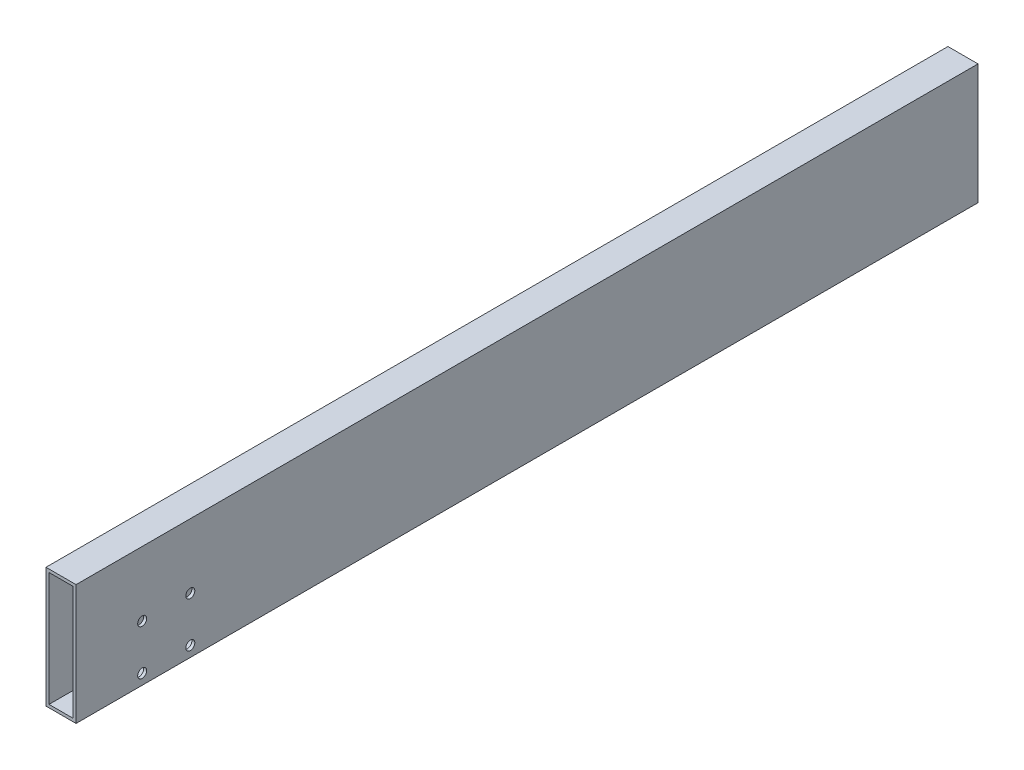
SolidWorks part; units mm, degrees
material "3.0205 (EN-AW 1200)"
ref_plane "前视基准面" through (0, 0, 0) normal (0, 0, 1) x (1, 0, 0)
ref_plane "上视基准面" through (0, 0, 0) normal (0, 1, 0) x (1, 0, 0)
ref_plane "右视基准面" through (0, 0, 0) normal (1, 0, 0) x (0, 0, -1)
sketch "草图1" plane through (0, 0, 0) normal (0, 0, 1) x (1, 0, 0)
  line L1 (0, 0) -> (10, 0)
  line L2 (0, 0) -> (0, 40)
  line L3 (0, 40) -> (10, 40)
  line L4 (10, 0) -> (10, 40)
  line L5 (1, 1) -> (9, 1)
  line L6 (1, 1) -> (1, 39)
  line L7 (1, 39) -> (9, 39)
  line L8 (9, 1) -> (9, 39)
  dimension "D1" = 10
  dimension "D2" = 40
  dimension "D3" = 1
  dimension "D4" = 1
  dimension "D5" = 1
  dimension "D6" = 1
extrude "凸台-拉伸1" add sketch "草图1" along normal blind 300
sketch "草图3" plane through (10, 0, 0) normal (1, 0, 0) x (0, 0, -1)
  line L0 (-300, 0) -> (-300, 40) construction
  line L1 (-278, 18.5) -> (-262, 18.5) construction
  line L2 (-278, 18.5) -> (-278, 3.5) construction
  line L3 (-278, 3.5) -> (-262, 3.5) construction
  line L4 (-262, 18.5) -> (-262, 3.5) construction
  line L5 (-300, 0) -> (0, 0) construction
  circle A0 centre (-278, 18.5) radius 1.5
  circle A1 centre (-262, 18.5) radius 1.5
  circle A2 centre (-262, 3.5) radius 1.5
  circle A3 centre (-278, 3.5) radius 1.5
  dimension "D5" = 3
  dimension "D6" = 3
  dimension "D7" = 3
  dimension "D8" = 3
  dimension "D1" = 22
  dimension "D2" = 16
  dimension "D3" = 15
  dimension "D4" = 3.5
extrude "切除-拉伸2" cut sketch "草图3" against normal blind 10
